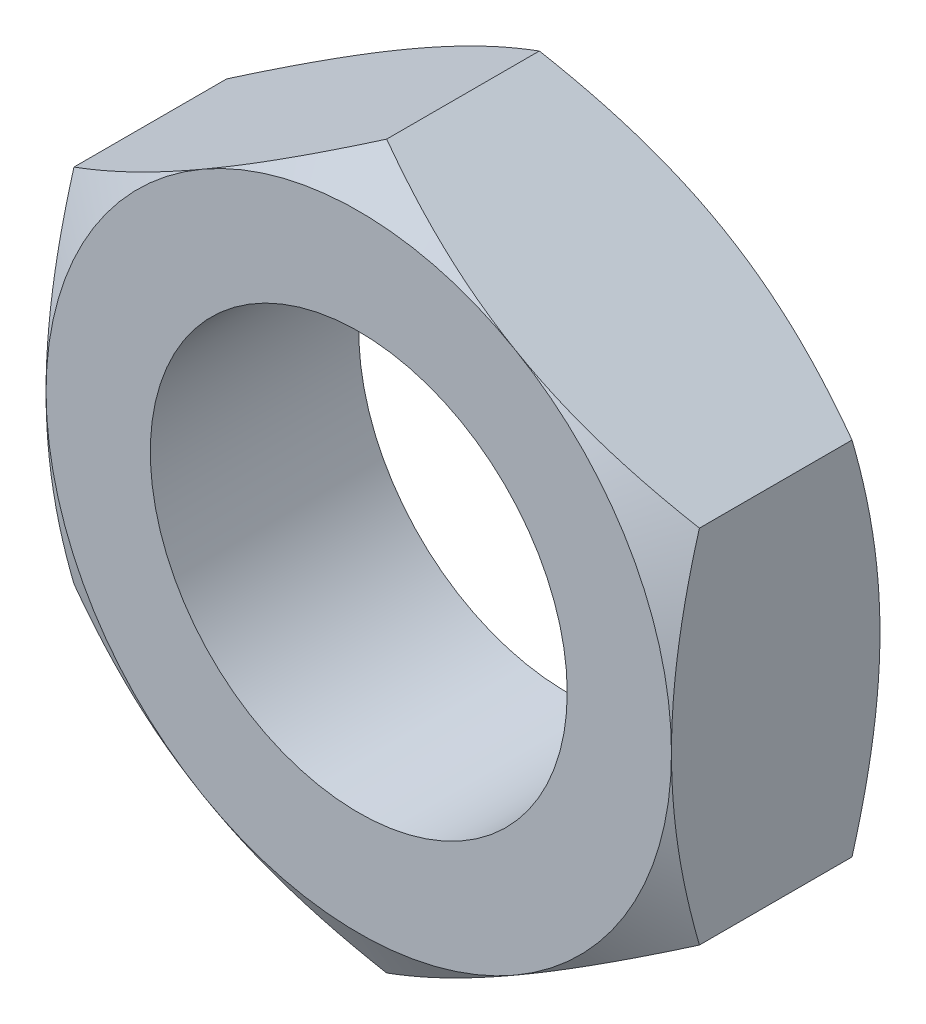
SolidWorks part; units mm, degrees
material "1.4000 (X6Cr13)"
ref_plane "Płaszczyzna przednia" through (0, 0, 0) normal (0, 0, 1) x (1, 0, 0)
ref_plane "Płaszczyzna górna" through (0, 0, 0) normal (0, 1, 0) x (1, 0, 0)
ref_plane "Płaszczyzna prawa" through (0, 0, 0) normal (1, 0, 0) x (0, 0, -1)
sketch "Szkic1" plane through (0, 0, 0) normal (0, 0, 1) x (1, 0, 0)
  line L1 (-15, 8.6603) -> (-15, -8.6603)
  line L2 (-15, -8.6603) -> (0, -17.3205)
  line L3 (0, -17.3205) -> (15, -8.6603)
  line L4 (15, -8.6603) -> (15, 8.6603)
  line L5 (15, 8.6603) -> (0, 17.3205)
  line L6 (0, 17.3205) -> (-15, 8.6603)
  circle A0 centre (0, 0) radius 10
  circle A1 centre (0, 0) radius 15 construction
  dimension "d" = 20
  dimension "s" = 30
extrude "Dodanie-wyciągnięcie1" add sketch "Szkic1" along normal mid plane 10
sketch "Szkic2" plane through (0, 0, 5) normal (0, 0, 1) x (1, 0, 0)
  circle A0 centre (0, 0) radius 15
  dimension "D1" = 30
extrude "Wytnij-wyciągnięcie2" cut sketch "Szkic2" against normal blind 10 draft 60 flip side to cut
mirror "Lustro1" about plane through (0, 0, 0) normal (0, 0, 1) of "Wytnij-wyciągnięcie2"
equation "\"D1@Szkic2\" = \"s@Szkic1\""
equation "\"D1@Wytnij-wyciągnięcie2\" = \"m@Dodanie-wyciągnięcie1\""
